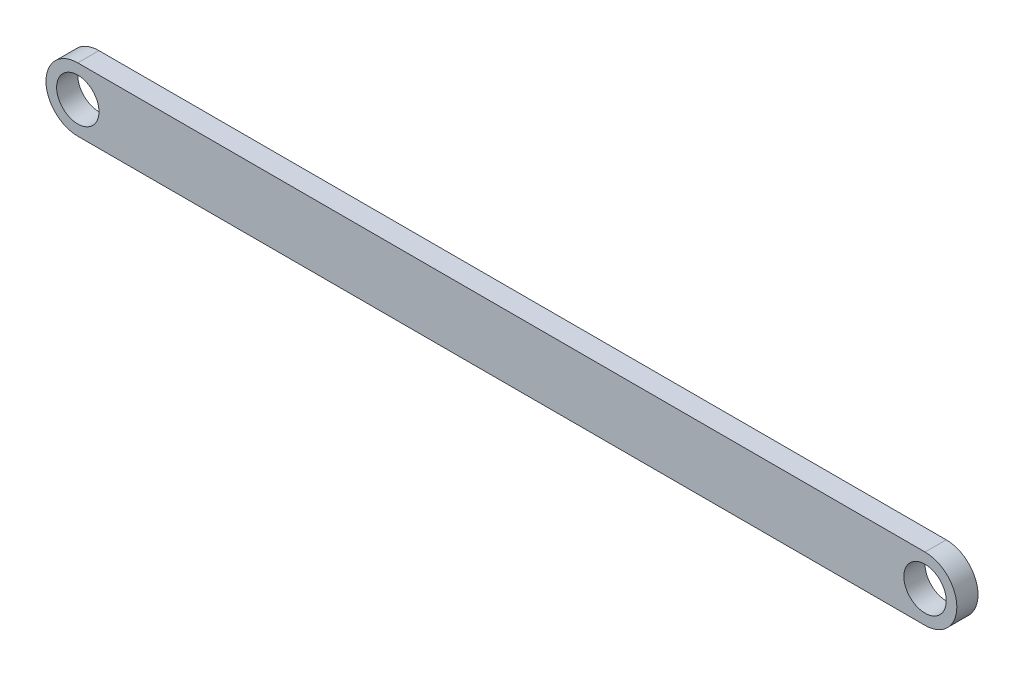
SolidWorks part; units mm, degrees
ref_plane "Front Plane" through (0, 0, 0) normal (0, 0, 1) x (1, 0, 0)
ref_plane "Top Plane" through (0, 0, 0) normal (0, 1, 0) x (1, 0, 0)
ref_plane "Right Plane" through (0, 0, 0) normal (1, 0, 0) x (0, 0, -1)
sketch "Sketch1" plane through (0, 0, 0) normal (0, 0, 1) x (1, 0, 0)
  line L0 (-192.9314, 0) -> (207.0686, 0) construction
  line L1 (-192.9314, 15) -> (207.0686, 15)
  line L2 (-192.9314, -15) -> (207.0686, -15)
  arc A0 (-192.9314, 15) -> (-192.9314, -15) centre (-192.9314, 0) ccw
  arc A1 (207.0686, -15) -> (207.0686, 15) centre (207.0686, 0) ccw
  circle A2 centre (-192.9314, 0) radius 10
  circle A3 centre (207.0686, 0) radius 10
  point P3 (7.0686, 0)
  dimension "D2" = 20
  dimension "D3" = 20
  dimension "D4" = 15
  dimension "D1" = 400
extrude "Boss-Extrude1" add sketch "Sketch1" along normal blind 10
